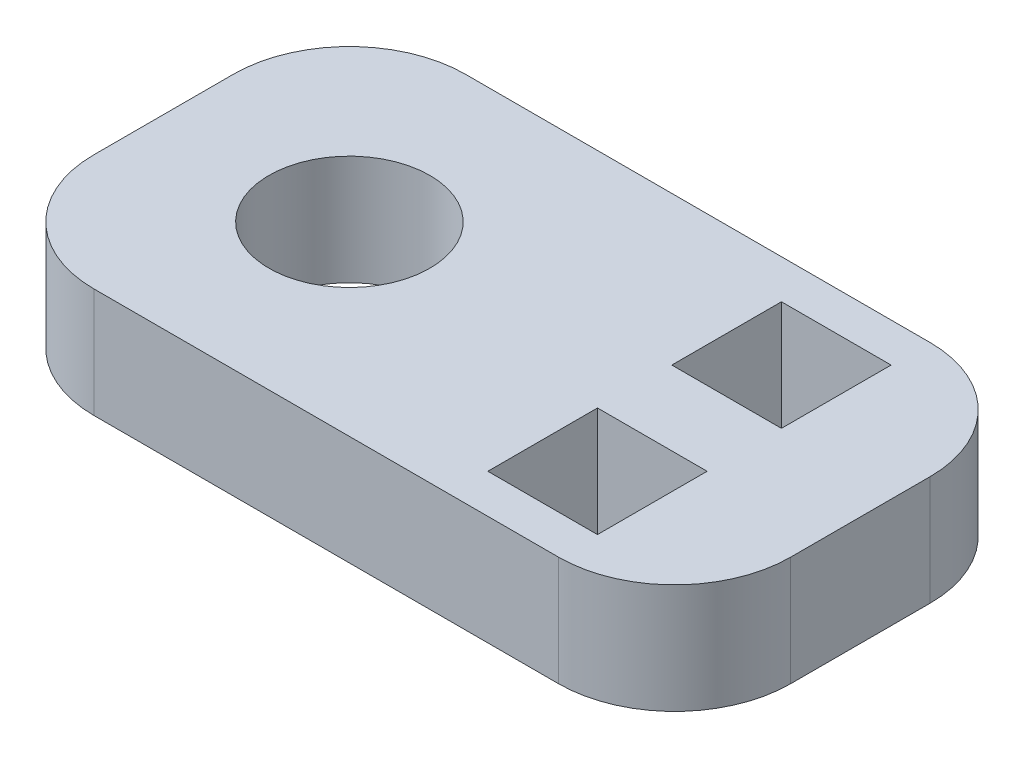
SolidWorks part; units mm, degrees
material "Acrylic (Medium-high impact)"
ref_plane "Front Plane" through (0, 0, 0) normal (0, 0, 1) x (1, 0, 0)
ref_plane "Top Plane" through (0, 0, 0) normal (0, 1, 0) x (1, 0, 0)
ref_plane "Right Plane" through (0, 0, 0) normal (1, 0, 0) x (0, 0, -1)
sketch "Sketch1" plane through (0, 0, 0) normal (0, 1, 0) x (1, 0, 0)
  line L0 (0, 5.08) -> (19.05, 5.08) construction
  line L1 (0, 0) -> (19.05, 0)
  line L2 (0, 0) -> (0, 10.16)
  line L3 (0, 10.16) -> (19.05, 10.16)
  line L4 (19.05, 0) -> (19.05, 10.16)
  line L5 (15.875, 1.0668) -> (15.875, 4.064)
  line L6 (12.8778, 9.0932) -> (15.875, 9.0932)
  line L7 (12.8778, 9.0932) -> (12.8778, 6.096)
  line L8 (12.8778, 6.096) -> (15.875, 6.096)
  line L9 (15.875, 9.0932) -> (15.875, 6.096)
  line L10 (12.8778, 4.064) -> (15.875, 4.064)
  line L11 (12.8778, 1.0668) -> (12.8778, 4.064)
  line L12 (12.8778, 1.0668) -> (15.875, 1.0668)
  circle A0 centre (5.08, 5.08) radius 2.2
  dimension "D1" = 4.4
  dimension "D2" = 19.05
  dimension "D3" = 5.08
  dimension "D4" = 10.16
  dimension "D5" = 1.016
  dimension "D6" = 2.9972
  dimension "D7" = 2.9972
  dimension "D8" = 3.175
extrude "Boss-Extrude1" add sketch "Sketch1" along normal blind 2.9972
fillet "Fillet1" radius 3.175 4 edges at (19.05, 1.4986, 0) (19.05, 1.4986, -10.16) (0, 1.4986, -10.16) (0, 1.4986, 0)
